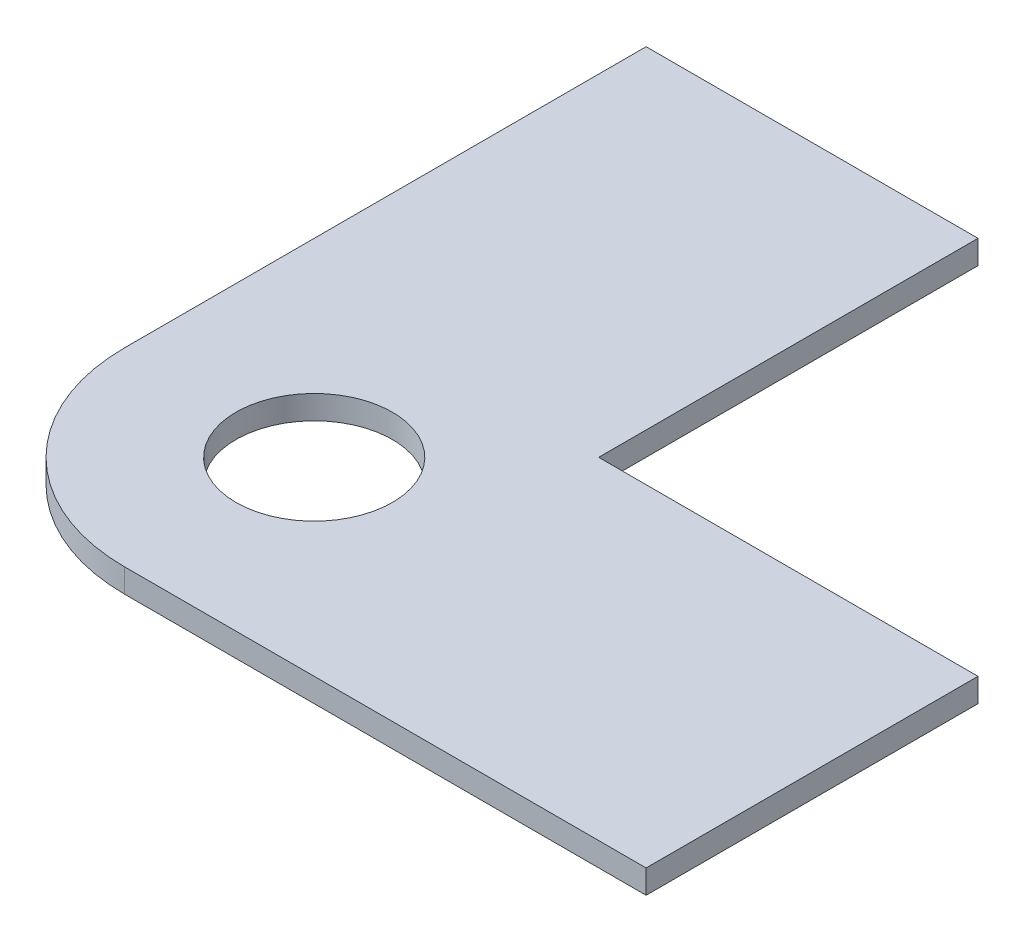
SolidWorks part; units mm, degrees
ref_plane "Front Plane" through (0, 0, 0) normal (0, 0, 1) x (1, 0, 0)
ref_plane "Top Plane" through (0, 0, 0) normal (0, 1, 0) x (1, 0, 0)
ref_plane "Right Plane" through (0, 0, 0) normal (1, 0, 0) x (0, 0, -1)
sketch "Sketch1" plane through (0, 0, 0) normal (0, 1, 0) x (1, 0, 0)
  line L0 (0, 0) -> (0, 11)
  line L1 (0, 0) -> (11, 0)
  line L2 (11, 0) -> (11, 3)
  line L3 (0, 11) -> (3, 11)
  line L4 (-3.9997, 0) -> (-3.9997, 11)
  line L5 (-3.9997, 11) -> (0, 11)
  line L6 (0, -3.9997) -> (11, -3.9997)
  line L7 (11, -3.9997) -> (11, 0)
  line L8 (3, 11) -> (3, 3)
  line L9 (3, 3) -> (11, 3)
  circle A0 centre (0, 0) radius 1.65
  arc A1 (0, -3.9997) -> (-3.9997, 0) centre (0, 0) cw
extrude "Boss-Extrude1" add sketch "Sketch1" along normal blind 0.5 contours A0 L1 L2 L9 L8 L3 L0 | A1 L6 L7 L1 A0 L0 L5 L4
